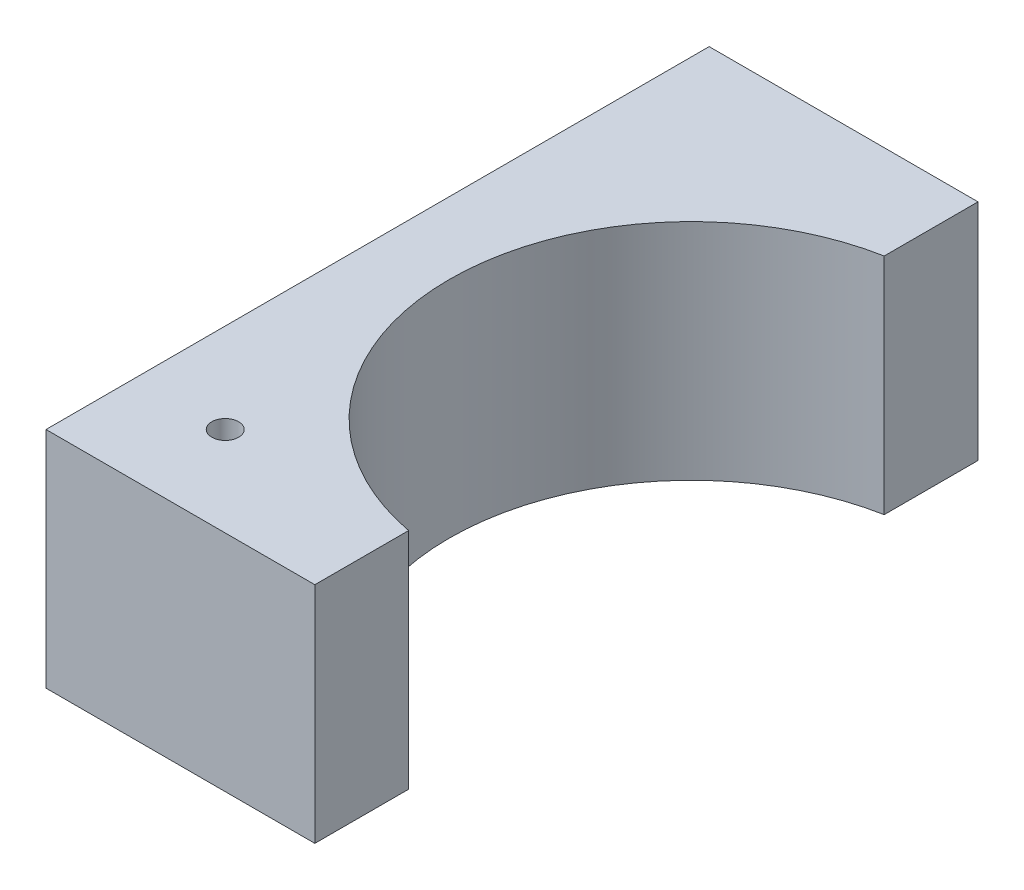
SolidWorks part; units mm, degrees
material "Balsa"
ref_plane "Front Plane" through (0, 0, 0) normal (0, 0, 1) x (1, 0, 0)
ref_plane "Top Plane" through (0, 0, 0) normal (0, 1, 0) x (1, 0, 0)
ref_plane "Right Plane" through (0, 0, 0) normal (1, 0, 0) x (0, 0, -1)
sketch "Sketch1" plane through (0, 0, 0) normal (0, 1, 0) x (1, 0, 0)
  line L0 (0, 0) -> (0, 148)
  line L1 (0, 148) -> (70, 148)
  line L2 (70, 148) -> (70, 128)
  line L3 (70, 20) -> (70, 0)
  line L4 (70, 0) -> (0, 0)
  arc A0 (70, 128) -> (70, 20) centre (70, 74) ccw
  circle A1 centre (20, 20) radius 3
  dimension "D1" = 54
  dimension "D5" = 6
  dimension "D2" = 20
  dimension "D3" = 20
  dimension "D4" = 70
  dimension "D6" = 20
  dimension "D7" = 20
extrude "Boss-Extrude1" add sketch "Sketch1" along normal blind 50
sketch "Sketch2" plane through (0, 50, 0) normal (0, 1, 0) x (1, 0, 0)
  line L0 (70, 148) -> (0, 148) construction
  line L1 (60, 148) -> (70, 148)
  line L2 (60, 148) -> (60, 0)
  line L3 (60, 0) -> (70, 0)
  line L4 (70, 148) -> (70, 0)
  dimension "D1" = 10
extrude "Cut-Extrude1" cut sketch "Sketch2" against normal through all
